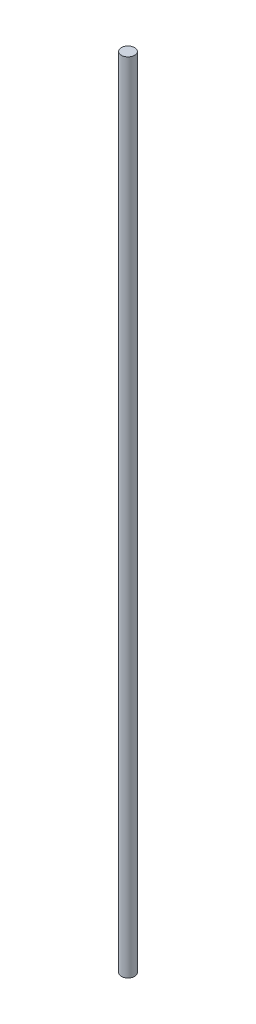
SolidWorks part; units mm, degrees
ref_plane "Plano frontal" through (0, 0, 0) normal (0, 0, 1) x (1, 0, 0)
ref_plane "Plano superior" through (0, 0, 0) normal (0, 1, 0) x (1, 0, 0)
ref_plane "Plano direito" through (0, 0, 0) normal (1, 0, 0) x (0, 0, -1)
sketch "Esboço1" plane through (0, 0, 0) normal (0, 1, 0) x (1, 0, 0)
  circle A0 centre (0, 0) radius 2.5
  dimension "D1" = 5
extrude "Ressalto-extrusão1" add sketch "Esboço1" along normal blind 299
